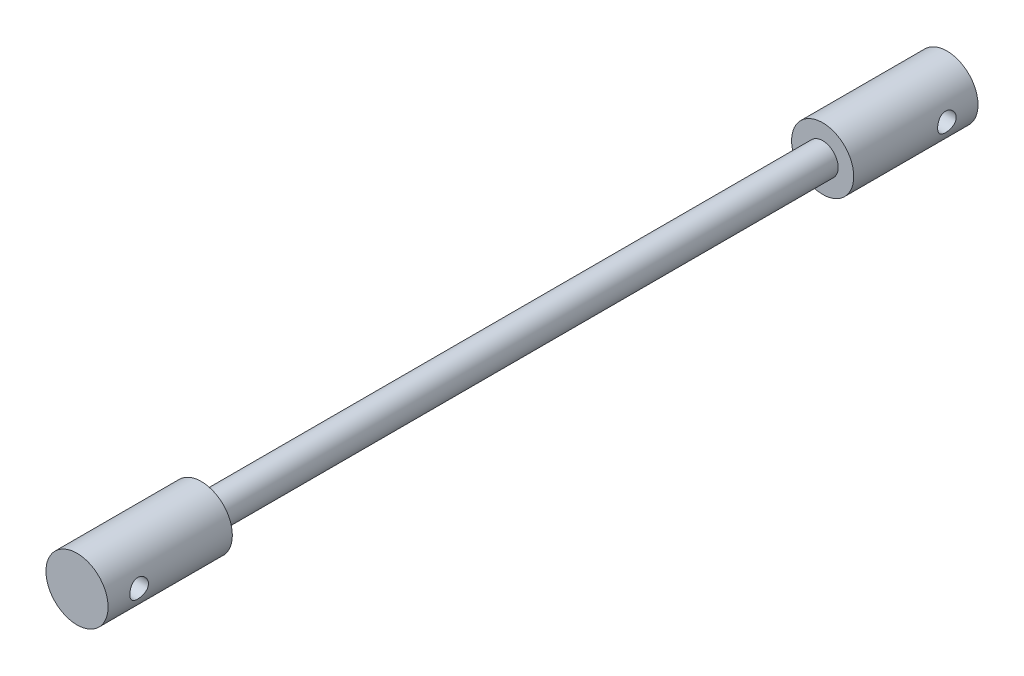
SolidWorks part; units mm, degrees
ref_plane "Front Plane" through (0, 0, 0) normal (0, 0, 1) x (1, 0, 0)
ref_plane "Top Plane" through (0, 0, 0) normal (0, 1, 0) x (1, 0, 0)
ref_plane "Right Plane" through (0, 0, 0) normal (1, 0, 0) x (0, 0, -1)
sketch "Sketch1" plane through (0, 0, 0) normal (0, 0, 1) x (1, 0, 0)
  circle A0 centre (0, 0) radius 5
  dimension "D1" = 10
extrude "Boss-Extrude1" add sketch "Sketch1" along normal blind 20
sketch "Sketch3" plane through (0, 0, 20) normal (0, 0, 1) x (1, 0, 0)
  circle A0 centre (0, 0) radius 2.5
  dimension "D1" = 5
extrude "Boss-Extrude2" add sketch "Sketch3" along normal blind 50
ref_plane "Plane1" through (5, 0, 0) normal (1, 0, 0) x (0, 0, -1)
sketch "Sketch7" plane through (5, 0, 0) normal (1, 0, 0) x (0, 0, -1)
  line L0 (0, 0) -> (-20, 0) construction
  line L1 (-20, 5) -> (-20, -5) construction
  circle A0 centre (-5, 0) radius 1.5
  dimension "D1" = 3
  dimension "D2" = 5
extrude "Cut-Extrude1" cut sketch "Sketch7" against normal through all
ref_plane "Plane2" through (0, 0, 70) normal (0, 0, 1) x (1, 0, 0)
mirror "Mirror4" about plane through (0, 0, 70) normal (0, 0, 1) of "Boss-Extrude2"
mirror "Mirror5" about plane through (0, 0, 70) normal (0, 0, 1) of "Boss-Extrude1"
sketch "Sketch9" plane through (5, 0, 0) normal (1, 0, 0) x (0, 0, -1)
  line L0 (0, 0) -> (-140, 0) construction
  line L1 (-140, 5) -> (-140, -5) construction
  circle A0 centre (-135, 0) radius 1.5
  dimension "D1" = 3
  dimension "D2" = 5
extrude "Cut-Extrude2" cut sketch "Sketch9" against normal through all
